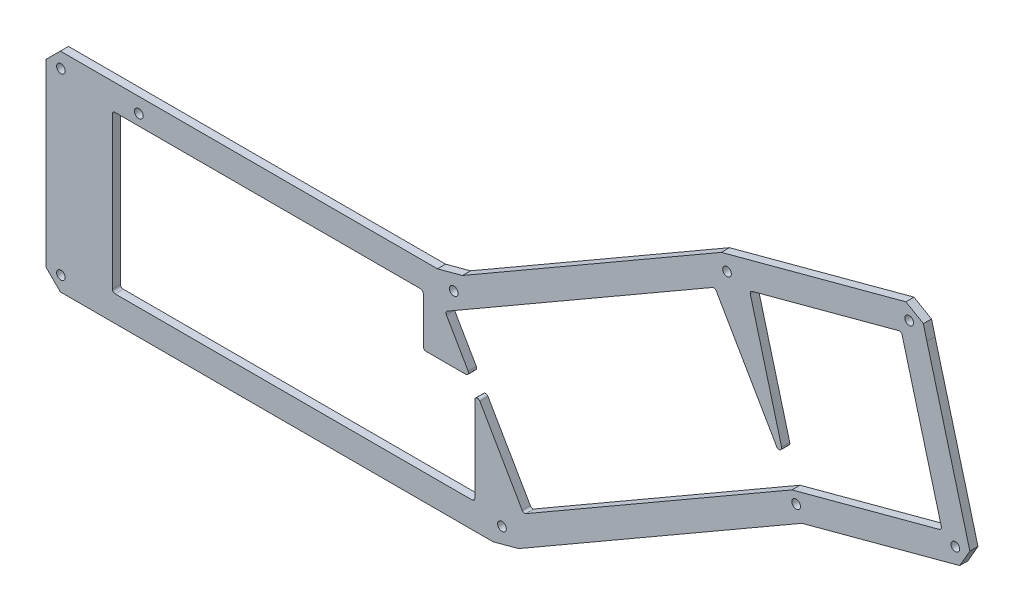
SolidWorks part; units mm, degrees
ref_plane "Plan de face" through (0, 0, 0) normal (0, 0, 1) x (1, 0, 0)
ref_plane "Plan de dessus" through (0, 0, 0) normal (0, 1, 0) x (1, 0, 0)
ref_plane "Plan de droite" through (0, 0, 0) normal (1, 0, 0) x (0, 0, -1)
sketch "Esquisse1" plane through (0, 0, 0) normal (0, 0, 1) x (1, 0, 0)
  line L0 (-73.9886, 18.0851) -> (-59.9886, 18.0851) construction
  line L1 (-73.9886, 37.0851) -> (-59.9886, 37.0851) construction
  line L2 (-73.9886, 37.0851) -> (-73.9886, 23.0851) construction
  line L3 (-73.9886, 23.0851) -> (-59.9886, 23.0851) construction
  line L4 (-59.9886, 37.0851) -> (-59.9886, 23.0851) construction
  line L5 (-73.9886, 18.0851) -> (-73.9886, 4.0851) construction
  line L6 (-73.9886, 4.0851) -> (-59.9886, 4.0851) construction
  line L7 (-59.9886, 18.0851) -> (-59.9886, 4.0851) construction
  line L8 (-73.9886, -0.9149) -> (-59.9886, -0.9149) construction
  line L9 (-73.9886, -0.9149) -> (-73.9886, -14.9149) construction
  line L10 (-73.9886, -14.9149) -> (-59.9886, -14.9149) construction
  line L11 (-59.9886, -0.9149) -> (-59.9886, -14.9149) construction
  line L12 (-73.9886, 37.0851) -> (-73.9886, 18.0851) construction
  line L13 (-54.9886, 18.0851) -> (-40.9886, 18.0851) construction
  line L14 (-54.9886, 37.0851) -> (-40.9886, 37.0851) construction
  line L15 (-54.9886, 37.0851) -> (-54.9886, 23.0851) construction
  line L16 (-54.9886, 23.0851) -> (-40.9886, 23.0851) construction
  line L17 (-40.9886, 37.0851) -> (-40.9886, 23.0851) construction
  line L18 (-54.9886, 18.0851) -> (-54.9886, 4.0851) construction
  line L19 (-54.9886, 4.0851) -> (-40.9886, 4.0851) construction
  line L20 (-40.9886, 18.0851) -> (-40.9886, 4.0851) construction
  line L21 (-54.9886, -0.9149) -> (-40.9886, -0.9149) construction
  line L22 (-54.9886, -0.9149) -> (-54.9886, -14.9149) construction
  line L23 (-54.9886, -14.9149) -> (-40.9886, -14.9149) construction
  line L24 (-40.9886, -0.9149) -> (-40.9886, -14.9149) construction
  line L25 (-54.9886, 37.0851) -> (-54.9886, 18.0851) construction
  line L26 (-35.9886, 18.0851) -> (-21.9886, 18.0851) construction
  line L27 (-35.9886, 37.0851) -> (-21.9886, 37.0851) construction
  line L28 (-35.9886, 37.0851) -> (-35.9886, 23.0851) construction
  line L29 (-35.9886, 23.0851) -> (-21.9886, 23.0851) construction
  line L30 (-21.9886, 37.0851) -> (-21.9886, 23.0851) construction
  line L31 (-35.9886, 18.0851) -> (-35.9886, 4.0851) construction
  line L32 (-35.9886, 4.0851) -> (-21.9886, 4.0851) construction
  line L33 (-21.9886, 18.0851) -> (-21.9886, 4.0851) construction
  line L34 (-35.9886, -0.9149) -> (-21.9886, -0.9149) construction
  line L35 (-35.9886, -0.9149) -> (-35.9886, -14.9149) construction
  line L36 (-35.9886, -14.9149) -> (-21.9886, -14.9149) construction
  line L37 (-21.9886, -0.9149) -> (-21.9886, -14.9149) construction
  line L38 (-35.9886, 37.0851) -> (-35.9886, 18.0851) construction
  line L39 (-16.9886, 18.0851) -> (-2.9886, 18.0851) construction
  line L40 (-16.9886, 37.0851) -> (-2.9886, 37.0851) construction
  line L41 (-16.9886, 37.0851) -> (-16.9886, 23.0851) construction
  line L42 (-16.9886, 23.0851) -> (-2.9886, 23.0851) construction
  line L43 (-2.9886, 37.0851) -> (-2.9886, 23.0851) construction
  line L44 (-16.9886, 18.0851) -> (-16.9886, 4.0851) construction
  line L45 (-16.9886, 4.0851) -> (-2.9886, 4.0851) construction
  line L46 (-2.9886, 18.0851) -> (-2.9886, 4.0851) construction
  line L47 (-16.9886, -0.9149) -> (-2.9886, -0.9149) construction
  line L48 (-16.9886, -0.9149) -> (-16.9886, -14.9149) construction
  line L49 (-16.9886, -14.9149) -> (-2.9886, -14.9149) construction
  line L50 (-2.9886, -0.9149) -> (-2.9886, -14.9149) construction
  line L51 (-16.9886, 37.0851) -> (-16.9886, 18.0851) construction
  line L52 (2.0114, 18.0851) -> (16.0114, 18.0851) construction
  line L53 (2.0114, 37.0851) -> (16.0114, 37.0851) construction
  line L54 (2.0114, 37.0851) -> (2.0114, 23.0851) construction
  line L55 (2.0114, 23.0851) -> (16.0114, 23.0851) construction
  line L56 (16.0114, 37.0851) -> (16.0114, 23.0851) construction
  line L57 (2.0114, 18.0851) -> (2.0114, 4.0851) construction
  line L58 (2.0114, 4.0851) -> (16.0114, 4.0851) construction
  line L59 (16.0114, 18.0851) -> (16.0114, 4.0851) construction
  line L60 (2.0114, -0.9149) -> (16.0114, -0.9149) construction
  line L61 (2.0114, -0.9149) -> (2.0114, -14.9149) construction
  line L62 (2.0114, -14.9149) -> (16.0114, -14.9149) construction
  line L63 (16.0114, -0.9149) -> (16.0114, -14.9149) construction
  line L64 (2.0114, 37.0851) -> (2.0114, 18.0851) construction
  line L65 (21.0114, 18.0851) -> (35.0114, 18.0851) construction
  line L66 (21.0114, 37.0851) -> (35.0114, 37.0851) construction
  line L67 (21.0114, 37.0851) -> (21.0114, 23.0851) construction
  line L68 (21.0114, 23.0851) -> (35.0114, 23.0851) construction
  line L69 (35.0114, 37.0851) -> (35.0114, 23.0851) construction
  line L70 (21.0114, 18.0851) -> (21.0114, 4.0851) construction
  line L71 (21.0114, 4.0851) -> (35.0114, 4.0851) construction
  line L72 (35.0114, 18.0851) -> (35.0114, 4.0851) construction
  line L73 (21.0114, -0.9149) -> (35.0114, -0.9149) construction
  line L74 (21.0114, -0.9149) -> (21.0114, -14.9149) construction
  line L75 (21.0114, -14.9149) -> (35.0114, -14.9149) construction
  line L76 (35.0114, -0.9149) -> (35.0114, -14.9149) construction
  line L77 (21.0114, 37.0851) -> (21.0114, 18.0851) construction
  line L78 (40.0114, 18.0851) -> (54.0114, 18.0851) construction
  line L79 (148.4089, 106.303) -> (52.8277, 51.1192) construction
  line L80 (52.8277, 51.1192) -> (43.3704, 48.5851) construction
  line L81 (-76.7538, 39.0851) -> (-76.7538, -16.9149)
  line L82 (-95.7538, 44.0851) -> (-53.0442, 44.0851) construction
  line L83 (40.0114, 18.0851) -> (40.0114, 4.0851) construction
  line L84 (40.0114, 4.0851) -> (54.0114, 4.0851) construction
  line L85 (54.0114, 18.0851) -> (54.0114, 4.0851) construction
  line L86 (40.0114, -0.9149) -> (54.0114, -0.9149) construction
  line L87 (40.0114, -0.9149) -> (40.0114, -14.9149) construction
  line L88 (40.0114, -14.9149) -> (54.0114, -14.9149) construction
  line L89 (54.0114, -0.9149) -> (54.0114, -14.9149) construction
  line L90 (40.0114, 20.0851) -> (40.0114, 18.0851) construction
  line L91 (-73.9886, 18.0851) -> (-54.9886, 18.0851) construction
  line L92 (56.0114, 20.0851) -> (56.7532, 18.8002) construction
  line L93 (-66.9886, 37.0851) -> (-66.9886, 44.0851) construction
  line L94 (67.3933, 2.371) -> (74.3933, -9.7534) construction
  line L95 (146.1202, 94.012) -> (168.4398, 55.3534)
  line L96 (158.7183, 99.2303) -> (170.2717, 56.1122)
  line L97 (19.0114, 39.0851) -> (37.0114, 39.0851) construction
  line L98 (37.0114, 39.0851) -> (37.0114, 21.0851) construction
  line L99 (19.0114, 21.0851) -> (37.0114, 21.0851) construction
  line L100 (19.0114, 39.0851) -> (19.0114, 21.0851) construction
  line L101 (79.4363, 55.512) -> (88.4363, 39.9235) construction
  line L102 (88.4363, 39.9235) -> (72.8478, 30.9235) construction
  line L103 (63.8478, 46.512) -> (72.8478, 30.9235) construction
  line L104 (79.4363, 55.512) -> (63.8478, 46.512) construction
  line L105 (62.9818, 46.012) -> (71.9818, 30.4235) construction
  line L106 (71.9818, 30.4235) -> (56.3933, 21.4235) construction
  line L107 (47.3933, 37.012) -> (56.3933, 21.4235) construction
  line L108 (62.9818, 46.012) -> (47.3933, 37.012) construction
  line L109 (164.2542, 60.603) -> (148.6657, 51.603) construction
  line L110 (62.2497, 43.2799) -> (71.7497, 26.8254) construction
  line L111 (78.7042, 52.7799) -> (88.2042, 36.3254) construction
  line L112 (95.1587, 62.2799) -> (104.6587, 45.8254) construction
  line L113 (111.6132, 71.7799) -> (121.1132, 55.3254) construction
  line L114 (128.0677, 81.2799) -> (137.5677, 64.8254) construction
  line L115 (144.5221, 90.7799) -> (154.0221, 74.3254) construction
  line L116 (148.6657, 51.603) -> (157.6657, 36.0146) construction
  line L117 (69.1254, 3.371) -> (76.1254, -8.7534) construction
  line L118 (88.2497, -1.7534) -> (76.1254, -8.7534) construction
  line L119 (81.2497, 10.371) -> (88.2497, -1.7534) construction
  line L120 (81.2497, 10.371) -> (69.1254, 3.371) construction
  line L121 (59.6254, 19.8254) -> (66.6254, 7.7011) construction
  line L122 (78.7497, 14.7011) -> (66.6254, 7.7011) construction
  line L123 (71.7497, 26.8254) -> (78.7497, 14.7011) construction
  line L124 (50.1254, 36.2799) -> (57.1254, 24.1556) construction
  line L125 (69.2497, 31.1556) -> (57.1254, 24.1556) construction
  line L126 (62.2497, 43.2799) -> (69.2497, 31.1556) construction
  line L127 (62.2497, 43.2799) -> (50.1254, 36.2799) construction
  line L128 (71.7497, 26.8254) -> (59.6254, 19.8254) construction
  line L129 (85.5799, 12.871) -> (92.5799, 0.7466) construction
  line L130 (104.7042, 7.7466) -> (92.5799, 0.7466) construction
  line L131 (97.7042, 19.871) -> (104.7042, 7.7466) construction
  line L132 (97.7042, 19.871) -> (85.5799, 12.871) construction
  line L133 (76.0799, 29.3254) -> (83.0799, 17.2011) construction
  line L134 (95.2042, 24.2011) -> (83.0799, 17.2011) construction
  line L135 (88.2042, 36.3254) -> (95.2042, 24.2011) construction
  line L136 (66.5799, 45.7799) -> (73.5799, 33.6556) construction
  line L137 (85.7042, 40.6556) -> (73.5799, 33.6556) construction
  line L138 (78.7042, 52.7799) -> (85.7042, 40.6556) construction
  line L139 (78.7042, 52.7799) -> (66.5799, 45.7799) construction
  line L140 (88.2042, 36.3254) -> (76.0799, 29.3254) construction
  line L141 (102.0343, 22.371) -> (109.0343, 10.2466) construction
  line L142 (121.1587, 17.2466) -> (109.0343, 10.2466) construction
  line L143 (114.1587, 29.371) -> (121.1587, 17.2466) construction
  line L144 (114.1587, 29.371) -> (102.0343, 22.371) construction
  line L145 (92.5343, 38.8254) -> (99.5343, 26.7011) construction
  line L146 (111.6587, 33.7011) -> (99.5343, 26.7011) construction
  line L147 (104.6587, 45.8254) -> (111.6587, 33.7011) construction
  line L148 (83.0343, 55.2799) -> (90.0343, 43.1556) construction
  line L149 (102.1587, 50.1556) -> (90.0343, 43.1556) construction
  line L150 (95.1587, 62.2799) -> (102.1587, 50.1556) construction
  line L151 (95.1587, 62.2799) -> (83.0343, 55.2799) construction
  line L152 (104.6587, 45.8254) -> (92.5343, 38.8254) construction
  line L153 (118.4888, 31.871) -> (125.4888, 19.7466) construction
  line L154 (137.6132, 26.7466) -> (125.4888, 19.7466) construction
  line L155 (130.6132, 38.871) -> (137.6132, 26.7466) construction
  line L156 (130.6132, 38.871) -> (118.4888, 31.871) construction
  line L157 (108.9888, 48.3254) -> (115.9888, 36.2011) construction
  line L158 (128.1132, 43.2011) -> (115.9888, 36.2011) construction
  line L159 (121.1132, 55.3254) -> (128.1132, 43.2011) construction
  line L160 (99.4888, 64.7799) -> (106.4888, 52.6556) construction
  line L161 (118.6132, 59.6556) -> (106.4888, 52.6556) construction
  line L162 (111.6132, 71.7799) -> (118.6132, 59.6556) construction
  line L163 (111.6132, 71.7799) -> (99.4888, 64.7799) construction
  line L164 (121.1132, 55.3254) -> (108.9888, 48.3254) construction
  line L165 (134.9433, 41.371) -> (141.9433, 29.2466) construction
  line L166 (154.0677, 36.2466) -> (141.9433, 29.2466) construction
  line L167 (147.0677, 48.371) -> (154.0677, 36.2466) construction
  line L168 (147.0677, 48.371) -> (134.9433, 41.371) construction
  line L169 (125.4433, 57.8254) -> (132.4433, 45.7011) construction
  line L170 (144.5677, 52.7011) -> (132.4433, 45.7011) construction
  line L171 (137.5677, 64.8254) -> (144.5677, 52.7011) construction
  line L172 (115.9433, 74.2799) -> (122.9433, 62.1556) construction
  line L173 (135.0677, 69.1556) -> (122.9433, 62.1556) construction
  line L174 (128.0677, 81.2799) -> (135.0677, 69.1556) construction
  line L175 (128.0677, 81.2799) -> (115.9433, 74.2799) construction
  line L176 (137.5677, 64.8254) -> (125.4433, 57.8254) construction
  line L177 (151.3978, 50.871) -> (158.3978, 38.7466) construction
  line L178 (170.5221, 45.7466) -> (158.3978, 38.7466) construction
  line L179 (163.5221, 57.871) -> (170.5221, 45.7466) construction
  line L180 (163.5221, 57.871) -> (151.3978, 50.871) construction
  line L181 (141.8978, 67.3254) -> (148.8978, 55.2011) construction
  line L182 (161.0221, 62.2011) -> (148.8978, 55.2011) construction
  line L183 (154.0221, 74.3254) -> (161.0221, 62.2011) construction
  line L184 (132.3978, 83.7799) -> (139.3978, 71.6556) construction
  line L185 (151.5221, 78.6556) -> (139.3978, 71.6556) construction
  line L186 (144.5221, 90.7799) -> (151.5221, 78.6556) construction
  line L187 (144.5221, 90.7799) -> (132.3978, 83.7799) construction
  line L188 (154.0221, 74.3254) -> (141.8978, 67.3254) construction
  line L189 (173.2542, 45.0146) -> (157.6657, 36.0146) construction
  line L190 (164.2542, 60.603) -> (173.2542, 45.0146) construction
  line L191 (178.3169, 34.0986) -> (169.0534, 56.4627) construction
  line L192 (169.5193, 62.7839) -> (174.1781, 45.3972) construction
  line L193 (174.1781, 45.3972) -> (191.5647, 50.056) construction
  line L194 (186.906, 67.4426) -> (191.5647, 50.056) construction
  line L195 (162.1337, 98.0749) -> (167.0513, 79.7223) construction
  line L196 (169.5193, 62.7839) -> (186.906, 67.4426) construction
  line L197 (167.0513, 79.7223) -> (180.5742, 83.3457) construction
  line L198 (162.1337, 98.0749) -> (175.6567, 101.6983) construction
  line L199 (162.1337, 98.0749) -> (165.7572, 84.5519) construction
  line L200 (165.7572, 84.5519) -> (179.2801, 88.1754) construction
  line L201 (175.6567, 101.6983) -> (179.2801, 88.1754) construction
  line L202 (167.0513, 79.7223) -> (170.6747, 66.1993) construction
  line L203 (170.6747, 66.1993) -> (184.1977, 69.8228) construction
  line L204 (180.5742, 83.3457) -> (184.1977, 69.8228) construction
  line L205 (171.9688, 61.3697) -> (185.4918, 64.9932) construction
  line L206 (171.9688, 61.3697) -> (175.5923, 47.8467) construction
  line L207 (175.5923, 47.8467) -> (189.1152, 51.4702) construction
  line L208 (185.4918, 64.9932) -> (189.1152, 51.4702) construction
  line L209 (185.4038, 84.6398) -> (198.9268, 88.2633) construction
  line L210 (180.4863, 102.9924) -> (194.0092, 106.6159) construction
  line L211 (180.4863, 102.9924) -> (184.1097, 89.4695) construction
  line L212 (184.1097, 89.4695) -> (197.6327, 93.0929) construction
  line L213 (194.0092, 106.6159) -> (197.6327, 93.0929) construction
  line L214 (185.4038, 84.6398) -> (189.0273, 71.1169) construction
  line L215 (189.0273, 71.1169) -> (202.5503, 74.7403) construction
  line L216 (198.9268, 88.2633) -> (202.5503, 74.7403) construction
  line L217 (190.3214, 66.2873) -> (203.8444, 69.9107) construction
  line L218 (190.3214, 66.2873) -> (193.9449, 52.7643) construction
  line L219 (193.9449, 52.7643) -> (207.4678, 56.3878) construction
  line L220 (203.8444, 69.9107) -> (207.4678, 56.3878) construction
  line L221 (187.8719, 67.7015) -> (192.5307, 50.3148) construction
  line L222 (192.5307, 50.3148) -> (209.9173, 54.9735) construction
  line L223 (205.2586, 72.3602) -> (209.9173, 54.9735) construction
  line L224 (180.4863, 102.9924) -> (185.4038, 84.6398) construction
  line L225 (187.8719, 67.7015) -> (205.2586, 72.3602) construction
  line L226 (203.7564, 89.5574) -> (217.2794, 93.1809) construction
  line L227 (198.8389, 107.91) -> (212.3618, 111.5335) construction
  line L228 (198.8389, 107.91) -> (202.4623, 94.387) construction
  line L229 (202.4623, 94.387) -> (215.9853, 98.0105) construction
  line L230 (212.3618, 111.5335) -> (215.9853, 98.0105) construction
  line L231 (203.7564, 89.5574) -> (207.3799, 76.0344) construction
  line L232 (207.3799, 76.0344) -> (220.9029, 79.6579) construction
  line L233 (217.2794, 93.1809) -> (220.9029, 79.6579) construction
  line L234 (208.674, 71.2048) -> (222.197, 74.8283) construction
  line L235 (208.674, 71.2048) -> (212.2975, 57.6819) construction
  line L236 (212.2975, 57.6819) -> (225.8204, 61.3053) construction
  line L237 (222.197, 74.8283) -> (225.8204, 61.3053) construction
  line L238 (206.2245, 72.619) -> (210.8833, 55.2324) construction
  line L239 (210.8833, 55.2324) -> (228.2699, 59.8911) construction
  line L240 (223.6112, 77.2778) -> (228.2699, 59.8911) construction
  line L241 (198.8389, 107.91) -> (203.7564, 89.5574) construction
  line L242 (206.2245, 72.619) -> (223.6112, 77.2778) construction
  line L243 (167.0513, 79.7223) -> (185.4038, 84.6398) construction
  line L244 (38.0114, 20.0851) -> (56.0114, 20.0851) construction
  line L245 (56.0114, 20.0851) -> (56.0114, 2.0851) construction
  line L246 (38.0114, 2.0851) -> (56.0114, 2.0851) construction
  line L247 (38.0114, 20.0851) -> (38.0114, 2.0851) construction
  line L248 (72.4818, 29.5575) -> (56.8933, 20.5575) construction
  line L249 (56.8933, 20.5575) -> (65.8933, 4.969) construction
  line L250 (81.4818, 13.969) -> (65.8933, 4.969) construction
  line L251 (72.4818, 29.5575) -> (81.4818, 13.969) construction
  line L252 (56.8933, 20.5575) -> (57.6111, 19.3142) construction
  line L253 (164.6018, 81.1365) -> (169.2605, 63.7498) construction
  line L254 (169.2605, 63.7498) -> (186.6472, 68.4086) construction
  line L255 (181.9884, 85.7952) -> (186.6472, 68.4086) construction
  line L256 (164.6018, 81.1365) -> (181.9884, 85.7952) construction
  line L257 (154.7542, 77.0575) -> (163.7542, 61.469) construction
  line L258 (163.7542, 61.469) -> (148.1657, 52.469) construction
  line L259 (139.1657, 68.0575) -> (148.1657, 52.469) construction
  line L260 (154.7542, 77.0575) -> (139.1657, 68.0575) construction
  line L261 (196.3894, 109.3242) -> (213.776, 113.983) construction
  line L262 (-94.7538, 35.7952) -> (-76.7538, 35.7952) construction
  line L263 (-94.7538, 35.7952) -> (-94.7538, 2.7952) construction
  line L264 (-94.7538, 2.7952) -> (-76.7538, 2.7952) construction
  line L265 (-75.9886, 48.5851) -> (43.3704, 48.5851) construction
  line L266 (213.776, 113.983) -> (218.4348, 96.5963) construction
  line L267 (201.0481, 91.9375) -> (218.4348, 96.5963) construction
  line L268 (196.3894, 109.3242) -> (201.0481, 91.9375) construction
  line L269 (-75.9886, -16.9149) -> (-57.9886, -16.9149) construction
  line L270 (-57.9886, 1.0851) -> (-57.9886, -16.9149) construction
  line L271 (-75.9886, 1.0851) -> (-57.9886, 1.0851) construction
  line L272 (-75.9886, 1.0851) -> (-75.9886, -16.9149) construction
  line L273 (38.0114, -16.9149) -> (56.0114, -16.9149) construction
  line L274 (56.0114, 1.0851) -> (56.0114, -16.9149) construction
  line L275 (38.0114, 1.0851) -> (56.0114, 1.0851) construction
  line L276 (38.0114, 1.0851) -> (38.0114, -16.9149) construction
  line L277 (-75.9886, 39.0851) -> (-57.9886, 39.0851) construction
  line L278 (-57.9886, 39.0851) -> (-57.9886, 21.0851) construction
  line L279 (-75.9886, 21.0851) -> (-57.9886, 21.0851) construction
  line L280 (-75.9886, 39.0851) -> (-75.9886, 21.0851) construction
  line L281 (145.2542, 93.512) -> (129.6657, 84.512) construction
  line L282 (129.6657, 84.512) -> (138.6657, 68.9235) construction
  line L283 (154.2542, 77.9235) -> (138.6657, 68.9235) construction
  line L284 (145.2542, 93.512) -> (154.2542, 77.9235) construction
  line L285 (223.4353, 116.5711) -> (228.0941, 99.1845) construction
  line L286 (148.2159, 106.7689) -> (211.1879, 123.6422) construction
  line L287 (177.5508, 35.9482) -> (235.6877, 51.5259) construction
  line L288 (177.5508, 35.9482) -> (72.9989, -24.4149) construction
  line L289 (-95.7538, -26.9149) -> (63.6687, -26.9149) construction
  line L290 (-100.7538, 35.7952) -> (-100.7538, -21.9149) construction
  line L291 (-75.9886, 49.0851) -> (43.3046, 49.0851) construction
  line L292 (148.2159, 106.7689) -> (52.6347, 51.5851) construction
  line L293 (-75.9886, 49.0851) -> (-57.9886, 49.0851) construction
  line L294 (140.2542, 102.1722) -> (124.6657, 93.1722) construction
  line L295 (193.8012, 118.9835) -> (211.1879, 123.6422) construction
  line L296 (213.4714, 45.5731) -> (230.8581, 50.2318) construction
  line L297 (38.0114, -26.9149) -> (38.0114, -85.4624) construction
  line L298 (178.2542, 36.3543) -> (162.6657, 27.3543) construction
  line L299 (38.0114, -26.9149) -> (56.0114, -26.9149) construction
  line L300 (-100.7538, 2.7952) -> (-100.7538, -38.0419) construction
  line L301 (-100.7538, 35.7952) -> (-100.7538, 2.7952) construction
  line L302 (-75.9886, 49.0851) -> (-95.7538, 49.0851) construction
  line L303 (-100.7538, 44.0851) -> (-100.7538, 35.7952) construction
  line L304 (211.1879, 123.6422) -> (216.0732, 124.9512) construction
  line L305 (222.1691, 121.4083) -> (223.4353, 116.5711) construction
  line L306 (228.0941, 99.1845) -> (239.2233, 57.6497) construction
  line L307 (216.0732, 124.9512) -> (222.1691, 121.4083) construction
  line L308 (235.6877, 51.5259) -> (239.2233, 57.6497) construction
  line L309 (63.6687, -26.9149) -> (72.9989, -24.4149) construction
  line L310 (52.6347, 51.5851) -> (43.3046, 49.0851) construction
  line L311 (-95.7538, 49.0851) -> (-100.7538, 44.0851) construction
  line L312 (-100.7538, -21.9149) -> (-95.7538, -26.9149) construction
  line L313 (-95.7538, 49.0851) -> (-95.7538, 44.0851) construction
  line L314 (-95.7538, 44.0851) -> (-100.7538, 44.0851) construction
  line L315 (-95.7538, -26.9149) -> (-95.7538, -21.9149) construction
  line L316 (68.3338, -25.6649) -> (67.0397, -20.8353) construction
  line L317 (47.9697, 50.3351) -> (49.2637, 45.5055) construction
  line L318 (177.5508, 35.9482) -> (175.6374, 40.5676) construction
  line L319 (148.2159, 106.7689) -> (150.1293, 102.1495) construction
  line L320 (239.2233, 57.6497) -> (234.3936, 56.3556) construction
  line L321 (216.0732, 124.9512) -> (217.3634, 120.1206) construction
  line L322 (146.1202, 94.012) -> (155.1202, 78.4235) construction
  line L323 (-76.7538, 35.7952) -> (-96.7538, 35.7952) construction
  line L324 (148.6019, 105.8371) -> (53.0207, 50.6533) construction
  line L325 (163.6358, 80.8777) -> (168.2946, 63.491) construction
  line L326 (57.0114, 14.621) -> (57.0114, -16.9149)
  line L327 (-75.9886, 48.5851) -> (-95.5467, 48.5851) construction
  line L328 (-96.7538, 39.0851) -> (-96.7538, 1.0851) construction
  line L329 (53.0207, 50.6533) -> (43.4362, 48.0851) construction
  line L330 (-75.9886, 48.0851) -> (43.4362, 48.0851) construction
  line L331 (-75.9886, 48.0851) -> (-95.3395, 48.0851) construction
  line L332 (-95.3395, 48.0851) -> (-99.7538, 43.6709) construction
  line L333 (-99.7538, 43.6709) -> (-99.7538, 35.7952) construction
  line L334 (-99.7538, 35.7952) -> (-99.7538, -21.5007) construction
  line L335 (-99.7538, -21.5007) -> (-95.3395, -25.9149) construction
  line L336 (-95.3395, -25.9149) -> (63.5371, -25.9149) construction
  line L337 (63.5371, -25.9149) -> (72.6129, -23.483) construction
  line L338 (177.1648, 36.88) -> (72.6129, -23.483) construction
  line L339 (177.1648, 36.88) -> (235.0288, 52.3847) construction
  line L340 (235.0288, 52.3847) -> (238.1501, 57.7909) construction
  line L341 (227.1281, 98.9257) -> (238.1501, 57.7909) construction
  line L342 (222.4686, 116.3151) -> (227.1281, 98.9257) construction
  line L343 (221.307, 120.7527) -> (222.4686, 116.3151) construction
  line L344 (215.9303, 123.8777) -> (221.307, 120.7527) construction
  line L345 (211.4467, 122.6763) -> (215.9303, 123.8777) construction
  line L346 (148.6019, 105.8371) -> (211.4467, 122.6763) construction
  line L347 (214.742, 114.2418) -> (229.2358, 60.1499)
  line L348 (174.0769, 44.3349) -> (228.5287, 58.9252)
  line L349 (174.0769, 44.3349) -> (75.8933, -12.3515)
  line L350 (159.4254, 100.455) -> (213.5172, 114.9489)
  line L351 (144.7542, 94.378) -> (46.8933, 37.878)
  line L352 (-75.7538, -17.9149) -> (56.0114, -17.9149)
  line L353 (-75.7538, 40.0851) -> (37.0114, 40.0851)
  line L354 (2.0114, 40.0851) -> (16.0114, 40.0851) construction
  line L355 (126.5677, 83.878) -> (114.4433, 76.878) construction
  line L356 (179.7098, 105.8902) -> (193.2328, 109.5137) construction
  line L357 (215.2596, 112.3099) -> (218.8831, 98.787) construction
  line L358 (194.7213, 49.8665) -> (208.2443, 53.49) construction
  line L359 (155.5677, 33.6485) -> (143.4433, 26.6485) construction
  line L360 (40.0114, -17.9149) -> (54.0114, -17.9149) construction
  line L361 (58.8774, 15.121) -> (74.5273, -11.9854)
  line L362 (66.5273, 1.871) -> (73.5273, -10.2534) construction
  line L363 (40.0114, 37.0851) -> (40.0114, 23.0851) construction
  line L364 (57.0114, 1.0851) -> (57.0114, -16.9149) construction
  line L365 (46.5273, 36.512) -> (54.568, 22.5851)
  line L366 (51.52, 37.0851) -> (54.0114, 37.0851) construction
  line L367 (40.0114, 23.0851) -> (54.0114, 23.0851) construction
  line L368 (39.0114, 21.0851) -> (53.702, 21.0851)
  line L369 (54.0114, 29.5492) -> (54.0114, 25.5492) construction
  line L370 (38.0114, 39.0851) -> (38.0114, 22.0851)
  line L371 (38.0114, 39.0851) -> (38.0114, 21.0851) construction
  line L372 (46.5273, 36.512) -> (55.5273, 20.9235) construction
  line L373 (-95.5467, 48.5851) -> (-100.2538, 43.878) construction
  line L374 (38.0114, 21.0851) -> (56.0114, 21.0851) construction
  line L375 (-100.2538, 43.878) -> (-100.2538, 35.7952) construction
  line L376 (-100.2538, 35.7952) -> (-100.2538, -21.7078) construction
  line L377 (-100.2538, -21.7078) -> (-95.5467, -26.4149) construction
  line L378 (-95.5467, -26.4149) -> (63.6029, -26.4149) construction
  line L379 (63.6029, -26.4149) -> (72.8059, -23.949) construction
  line L380 (177.3578, 36.4141) -> (72.8059, -23.949) construction
  line L381 (177.3578, 36.4141) -> (235.3583, 51.9553) construction
  line L382 (235.3583, 51.9553) -> (238.6867, 57.7203) construction
  line L383 (227.6111, 99.0551) -> (238.6867, 57.7203) construction
  line L384 (222.952, 116.4431) -> (227.6111, 99.0551) construction
  line L385 (221.738, 121.0805) -> (222.952, 116.4431) construction
  line L386 (216.0018, 124.4145) -> (221.738, 121.0805) construction
  line L387 (211.3173, 123.1592) -> (216.0018, 124.4145) construction
  line L388 (148.4089, 106.303) -> (211.3173, 123.1592) construction
  line L389 (-75.9886, 49.5851) -> (-95.9609, 49.5851)
  line L390 (-95.9609, 49.5851) -> (-101.2538, 44.2922)
  line L391 (-101.2538, 44.2922) -> (-101.2538, 35.7952)
  line L392 (-101.2538, 35.7952) -> (-101.2538, -22.122)
  line L393 (-101.2538, -22.122) -> (-95.9609, -27.4149)
  line L394 (-95.9609, -27.4149) -> (63.7346, -27.4149)
  line L395 (63.7346, -27.4149) -> (73.1918, -24.8808)
  line L396 (177.7438, 35.4823) -> (73.1918, -24.8808)
  line L397 (177.7438, 35.4823) -> (236.0172, 51.0966)
  line L398 (236.0172, 51.0966) -> (239.7598, 57.579)
  line L399 (228.577, 99.3139) -> (239.7598, 57.579)
  line L400 (223.9186, 116.6992) -> (228.577, 99.3139)
  line L401 (222.6001, 121.7361) -> (223.9186, 116.6992)
  line L402 (216.1447, 125.488) -> (222.6001, 121.7361)
  line L403 (211.0584, 124.1252) -> (216.1447, 125.488)
  line L404 (148.0229, 107.2348) -> (211.0584, 124.1252)
  line L405 (148.0229, 107.2348) -> (52.4417, 52.051)
  line L406 (52.4417, 52.051) -> (43.2388, 49.5851)
  line L407 (-75.9886, 49.5851) -> (43.2388, 49.5851)
  circle A0 centre (-95.7538, 44.0851) radius 1.5 construction
  circle A1 centre (-95.7538, -21.9149) radius 1.5 construction
  circle A2 centre (67.0397, -20.8353) radius 1.5 construction
  circle A3 centre (49.2637, 45.5055) radius 1.5 construction
  circle A4 centre (175.6374, 40.5676) radius 1.5 construction
  circle A5 centre (150.1293, 102.1495) radius 1.5 construction
  circle A6 centre (234.3936, 56.3556) radius 1.5 construction
  circle A7 centre (217.3634, 120.1206) radius 1.5 construction
  circle A8 centre (-66.9886, 44.0851) radius 1.5 construction
  arc A9 (168.4398, 55.3534) -> (170.2717, 56.1122) centre (169.3058, 55.8534) ccw
  arc A10 (57.0114, 14.621) -> (58.8774, 15.121) centre (58.0114, 14.621) cw
  arc A11 (53.702, 21.0851) -> (54.568, 22.5851) centre (53.702, 22.0851) ccw
  arc A12 (39.0114, 21.0851) -> (38.0114, 22.0851) centre (39.0114, 22.0851) cw
  arc A13 (-75.7538, 40.0851) -> (-76.7538, 39.0851) centre (-75.7538, 39.0851) ccw
  circle A14 centre (-95.7538, 44.0851) radius 1.6
  circle A15 centre (-66.9886, 44.0851) radius 1.6
  arc A16 (-76.7538, -16.9149) -> (-75.7538, -17.9149) centre (-75.7538, -16.9149) ccw
  arc A17 (228.5287, 58.9252) -> (229.2358, 60.1499) centre (228.2699, 59.8911) ccw
  arc A18 (214.742, 114.2418) -> (213.5172, 114.9489) centre (213.776, 113.983) ccw
  arc A19 (158.7183, 99.2303) -> (159.4254, 100.455) centre (159.6842, 99.4891) cw
  arc A20 (146.1202, 94.012) -> (144.7542, 94.378) centre (145.2542, 93.512) ccw
  arc A21 (57.0114, -16.9149) -> (56.0114, -17.9149) centre (56.0114, -16.9149) cw
  arc A22 (74.5273, -11.9854) -> (75.8933, -12.3515) centre (75.3933, -11.4854) ccw
  arc A23 (46.5273, 36.512) -> (46.8933, 37.878) centre (47.3933, 37.012) cw
  arc A24 (38.0114, 39.0851) -> (37.0114, 40.0851) centre (37.0114, 39.0851) ccw
  circle A25 centre (-95.7538, -21.9149) radius 1.6
  circle A26 centre (67.0397, -20.8353) radius 1.6
  circle A27 centre (49.2637, 45.5055) radius 1.6
  circle A28 centre (150.1293, 102.1495) radius 1.6
  circle A29 centre (217.3634, 120.1206) radius 1.6
  circle A30 centre (234.3936, 56.3556) radius 1.6
  circle A31 centre (175.6374, 40.5676) radius 1.6
  point P85 (40.0114, 37.0851)
  point P86 (54.0114, 23.0851)
  point P88 (54.0114, 37.0851)
  point P102 (38.0114, 39.0851)
  point P103 (56.0114, 39.0851)
  point P304 (48.3046, 49.0851)
  point P305 (240.5174, 52.82)
  point P308 (68.6687, -26.9149)
  point P309 (-100.7538, -26.9149)
  point P311 (-100.7538, 49.0851)
  point P312 (220.9029, 126.2453)
  point P409 (172.2377, 48.7752)
  dimension "D32" = 3
  dimension "D33" = 5
  dimension "D40" = 5
  dimension "D41" = 5
  dimension "D42" = 5
  dimension "D43" = 5
  dimension "D44" = 20
  dimension "D53" = 2
  dimension "D56" = 1
  dimension "D59" = 1
  dimension "D63" = 1
  dimension "D64" = 1
  dimension "D65" = 0.5
  dimension "D8" = 1
  dimension "D1" = 14
  dimension "D2" = 14
  dimension "D4" = 19
  dimension "D6" = 19
  dimension "D7" = 30
  dimension "D10" = 1
  dimension "D11" = 2
  dimension "D13" = 0.5
  dimension "D15" = 2
  dimension "D12" = 7.5
  dimension "D14" = 19
  dimension "D18" = 2
  dimension "D20" = 18
  dimension "D21" = 33
  dimension "D22" = 2
  dimension "D9" = 2
  dimension "D16" = 2
  dimension "D19" = 2
  dimension "D23" = 2
  dimension "D24" = 10
  dimension "D25" = 10
  dimension "D26" = 10
  dimension "D27" = 10
  dimension "D28" = 10
  dimension "D29" = 6
  dimension "D30" = 10
  dimension "D31" = 10
  dimension "D45" = 1
  dimension "D46" = 3
  dimension "D47" = 3
  dimension "D48" = 3
  dimension "D49" = 3
  dimension "D50" = 3
  dimension "D51" = 3
  dimension "D52" = 3
  dimension "D54" = 1
  dimension "D55" = 1
  dimension "D57" = 1
  dimension "D58" = 1
  dimension "D60" = 1
  dimension "D61" = 1
  dimension "D62" = 1
  dimension "D66" = 1
  dimension "D67" = 0.1
  dimension "D3" = 3
  dimension "D5" = 7
  dimension "D17" = 3
extrude "Boss.-Extru.1" add sketch "Esquisse1" along normal blind 3
